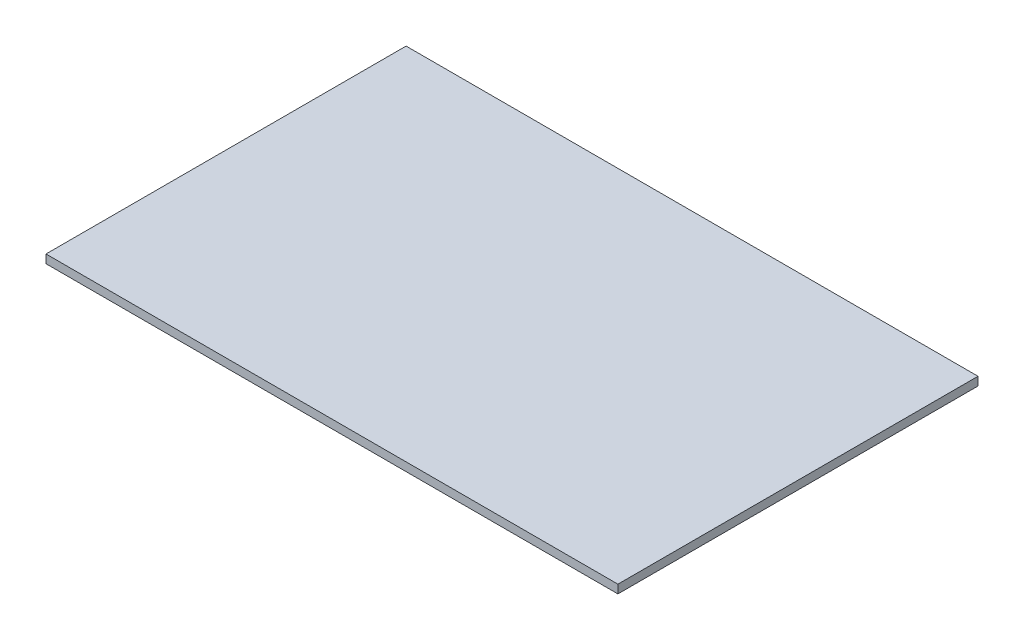
SolidWorks part; units mm, degrees
ref_plane "Front Plane" through (0, 0, 0) normal (0, 0, 1) x (1, 0, 0)
ref_plane "Top Plane" through (0, 0, 0) normal (0, 1, 0) x (1, 0, 0)
ref_plane "Right Plane" through (0, 0, 0) normal (1, 0, 0) x (0, 0, -1)
sketch "Sketch1" plane through (0, 0, 0) normal (0, 1, 0) x (1, 0, 0)
  line L1 (-67.5, -42.5) -> (67.5, -42.5)
  line L2 (-67.5, -42.5) -> (-67.5, 42.5)
  line L3 (-67.5, 42.5) -> (67.5, 42.5)
  line L4 (67.5, -42.5) -> (67.5, 42.5)
  line L5 (-67.5, -42.5) -> (67.5, 42.5) construction
  line L6 (-67.5, 42.5) -> (67.5, -42.5) construction
  point P0 (0, 0)
  dimension "D1" = 85
  dimension "D2" = 135
extrude "Boss-Extrude1" add sketch "Sketch1" along normal blind 2
